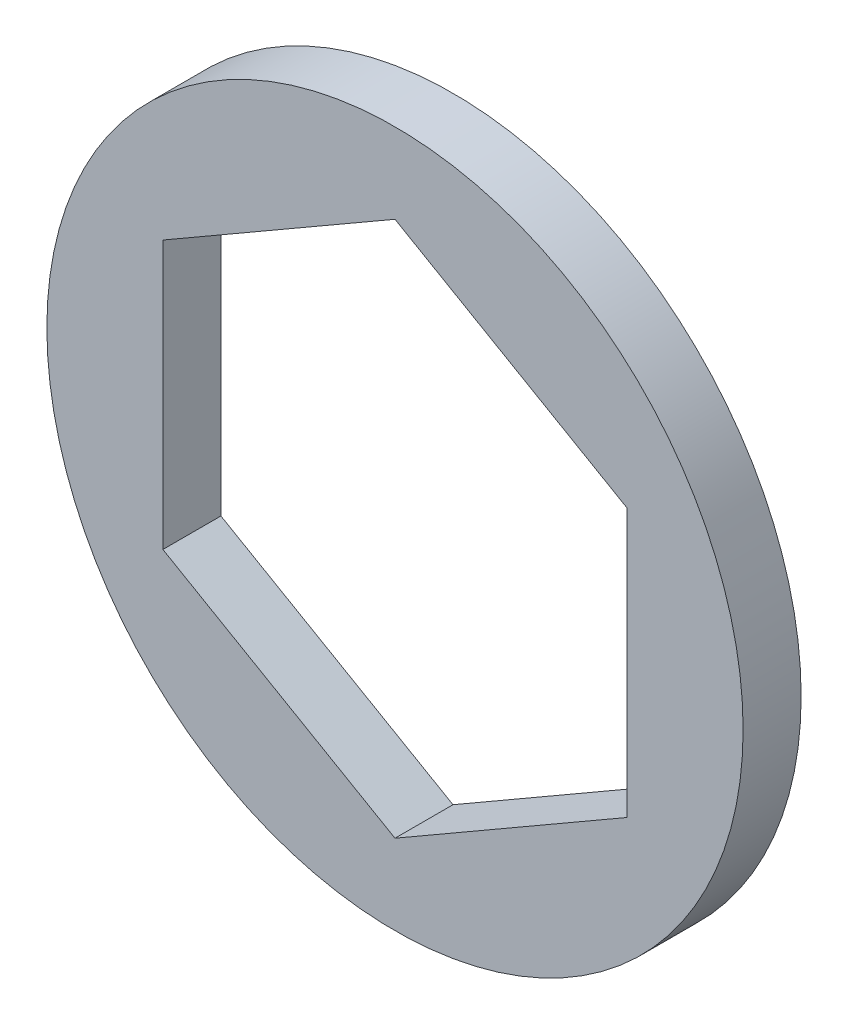
SolidWorks part; units mm, degrees
material "Nylon 101"
ref_plane "Front Plane" through (0, 0, 0) normal (0, 0, 1) x (1, 0, 0)
ref_plane "Top Plane" through (0, 0, 0) normal (0, 1, 0) x (1, 0, 0)
ref_plane "Right Plane" through (0, 0, 0) normal (1, 0, 0) x (0, 0, -1)
other "nylon"
sketch "Sketch1" plane through (0, 0, 0) normal (0, 0, 1) x (1, 0, 0)
  line L1 (0, 7.3323) -> (-6.35, 3.6662)
  line L2 (-6.35, 3.6662) -> (-6.35, -3.6662)
  line L3 (-6.35, -3.6662) -> (0, -7.3323)
  line L4 (0, -7.3323) -> (6.35, -3.6662)
  line L5 (6.35, -3.6662) -> (6.35, 3.6662)
  line L6 (6.35, 3.6662) -> (0, 7.3323)
  circle A0 centre (0, 0) radius 9.525
  circle A2 centre (0, 0) radius 6.35 construction
  point P3 (0, 0)
  dimension "D1" = 19.05
  dimension "D2" = 12.7
extrude "Boss-Extrude1" add sketch "Sketch1" along normal mid plane 1.5875
